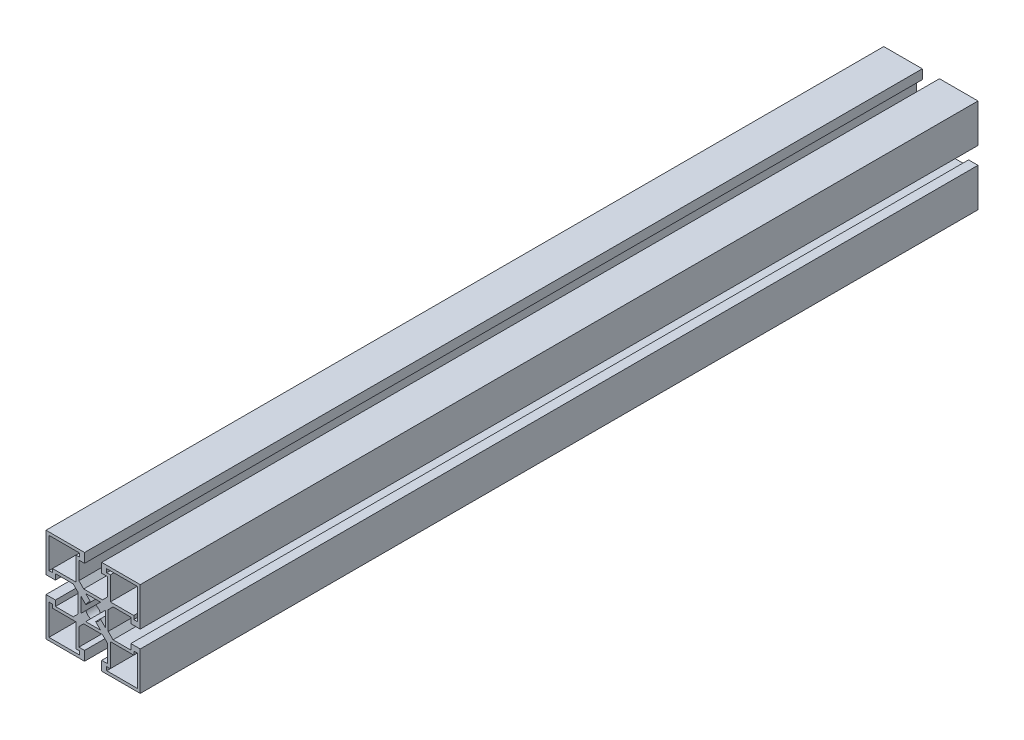
SolidWorks part; units mm, degrees
material "6061 Alloy"
ref_plane "Front Plane" through (0, 0, 0) normal (0, 0, 1) x (1, 0, 0)
ref_plane "Top Plane" through (0, 0, 0) normal (0, 1, 0) x (1, 0, 0)
ref_plane "Right Plane" through (0, 0, 0) normal (1, 0, 0) x (0, 0, -1)
sketch "Sketch1" plane through (0, 0, 0) normal (0, 0, 1) x (1, 0, 0)
  line L18 (8.2, 8.2) -> (8.2, 19.4)
  line L20 (19.4, 8.2) -> (8.2, 8.2)
  line L21 (19.4, 6.5) -> (19.4, 8.2)
  line L22 (21.1, 6.5) -> (19.4, 6.5)
  line L23 (21.1, 21.1) -> (21.1, 6.5)
  line L24 (6.5, 21.1) -> (21.1, 21.1)
  line L25 (6.5, 19.4) -> (6.5, 21.1)
  line L26 (8.2, 19.4) -> (6.5, 19.4)
  line L27 (-19.4, 6.5) -> (-21.1, 6.5)
  line L28 (-19.4, 8.2) -> (-19.4, 6.5)
  line L29 (-8.2, 8.2) -> (-19.4, 8.2)
  line L31 (-8.2, 19.4) -> (-8.2, 8.2)
  line L32 (-6.5, 19.4) -> (-8.2, 19.4)
  line L33 (-6.5, 21.1) -> (-6.5, 19.4)
  line L34 (-21.1, 21.1) -> (-6.5, 21.1)
  line L35 (-21.1, 6.5) -> (-21.1, 21.1)
  line L88 (-22.5, -22.5) -> (-4.1, -22.5)
  line L89 (-4.1, -22.5) -> (-4.1, -18)
  line L90 (-4.1, -18) -> (-6.8, -18)
  line L91 (-6.8, -18) -> (-6.8, -9.5)
  line L92 (-6.8, -9.5) -> (-4.5, -7.2)
  line L93 (-4.5, -7.2) -> (4.5, -7.2)
  line L94 (4.5, -7.2) -> (6.8, -9.5)
  line L95 (6.8, -9.5) -> (6.8, -18)
  line L96 (6.8, -18) -> (4.1, -18)
  line L97 (4.1, -18) -> (4.1, -22.5)
  line L98 (4.1, -22.5) -> (22.5, -22.5)
  line L99 (22.5, -22.5) -> (22.5, -4.1)
  line L100 (22.5, -4.1) -> (18, -4.1)
  line L101 (18, -4.1) -> (18, -6.8)
  line L102 (18, -6.8) -> (9.5, -6.8)
  line L103 (9.5, -6.8) -> (7.2, -4.5)
  line L104 (7.2, -4.5) -> (7.2, 4.5)
  line L105 (7.2, 4.5) -> (9.5, 6.8)
  line L106 (9.5, 6.8) -> (18, 6.8)
  line L107 (18, 6.8) -> (18, 4.1)
  line L108 (18, 4.1) -> (22.5, 4.1)
  line L109 (22.5, 4.1) -> (22.5, 22.5)
  line L110 (22.5, 22.5) -> (4.1, 22.5)
  line L111 (4.1, 22.5) -> (4.1, 18)
  line L112 (4.1, 18) -> (6.8, 18)
  line L113 (6.8, 18) -> (6.8, 9.5)
  line L114 (6.8, 9.5) -> (4.5, 7.2)
  line L115 (4.5, 7.2) -> (-4.5, 7.2)
  line L116 (-4.5, 7.2) -> (-6.8, 9.5)
  line L117 (-6.8, 9.5) -> (-6.8, 18)
  line L118 (-6.8, 18) -> (-4.1, 18)
  line L119 (-4.1, 18) -> (-4.1, 22.5)
  line L120 (-4.1, 22.5) -> (-22.5, 22.5)
  line L121 (-22.5, 22.5) -> (-22.5, 4.1)
  line L122 (-22.5, 4.1) -> (-18, 4.1)
  line L123 (-18, 4.1) -> (-18, 6.8)
  line L124 (-18, 6.8) -> (-9.5, 6.8)
  line L125 (-9.5, 6.8) -> (-7.2, 4.5)
  line L126 (-7.2, 4.5) -> (-7.2, -4.5)
  line L127 (-7.2, -4.5) -> (-9.5, -6.8)
  line L128 (-9.5, -6.8) -> (-18, -6.8)
  line L129 (-18, -6.8) -> (-18, -4.1)
  line L130 (-18, -4.1) -> (-22.5, -4.1)
  line L131 (-22.5, -4.1) -> (-22.5, -22.5)
  line L133 (-6.5, -21.1) -> (-21.1, -21.1)
  line L134 (-6.5, -19.4) -> (-6.5, -21.1)
  line L135 (-8.2, -19.4) -> (-6.5, -19.4)
  line L136 (-8.2, -8.2) -> (-8.2, -19.4)
  line L138 (-19.4, -8.2) -> (-8.2, -8.2)
  line L139 (-19.4, -6.5) -> (-19.4, -8.2)
  line L140 (-21.1, -6.5) -> (-19.4, -6.5)
  line L141 (-21.1, -21.1) -> (-21.1, -6.5)
  line L151 (6.5, -19.4) -> (8.2, -19.4)
  line L152 (6.5, -21.1) -> (6.5, -19.4)
  line L153 (21.1, -21.1) -> (6.5, -21.1)
  line L154 (21.1, -6.5) -> (21.1, -21.1)
  line L155 (19.4, -6.5) -> (21.1, -6.5)
  line L156 (19.4, -8.2) -> (19.4, -6.5)
  line L157 (8.2, -8.2) -> (19.4, -8.2)
  line L159 (8.2, -19.4) -> (8.2, -8.2)
  line L172 (-5.8, 3.5373) -> (-3.4511, 1.1884)
  line L173 (-5.8, -3.5373) -> (-5.8, 3.5373)
  line L174 (-3.4511, -1.1884) -> (-5.8, -3.5373)
  line L175 (-3.5373, -5.8) -> (-1.1884, -3.4511)
  line L176 (3.5373, -5.8) -> (-3.5373, -5.8)
  line L177 (1.1884, -3.4511) -> (3.5373, -5.8)
  line L178 (5.8, -3.5373) -> (3.4511, -1.1884)
  line L179 (5.8, 3.5373) -> (5.8, -3.5373)
  line L180 (3.4511, 1.1884) -> (5.8, 3.5373)
  line L181 (3.5373, 5.8) -> (1.1884, 3.4511)
  line L182 (-3.5373, 5.8) -> (3.5373, 5.8)
  line L183 (-1.1884, 3.4511) -> (-3.5373, 5.8)
  arc A4 (-1.1884, 3.4511) -> (-3.4511, 1.1884) centre (0, 0) ccw
  arc A5 (-3.4511, -1.1884) -> (-1.1884, -3.4511) centre (0, 0) ccw
  arc A6 (1.1884, -3.4511) -> (3.4511, -1.1884) centre (0, 0) ccw
  arc A7 (3.4511, 1.1884) -> (1.1884, 3.4511) centre (0, 0) ccw
extrude "Boss-Extrude1" add sketch "Sketch1" along normal blind 400
